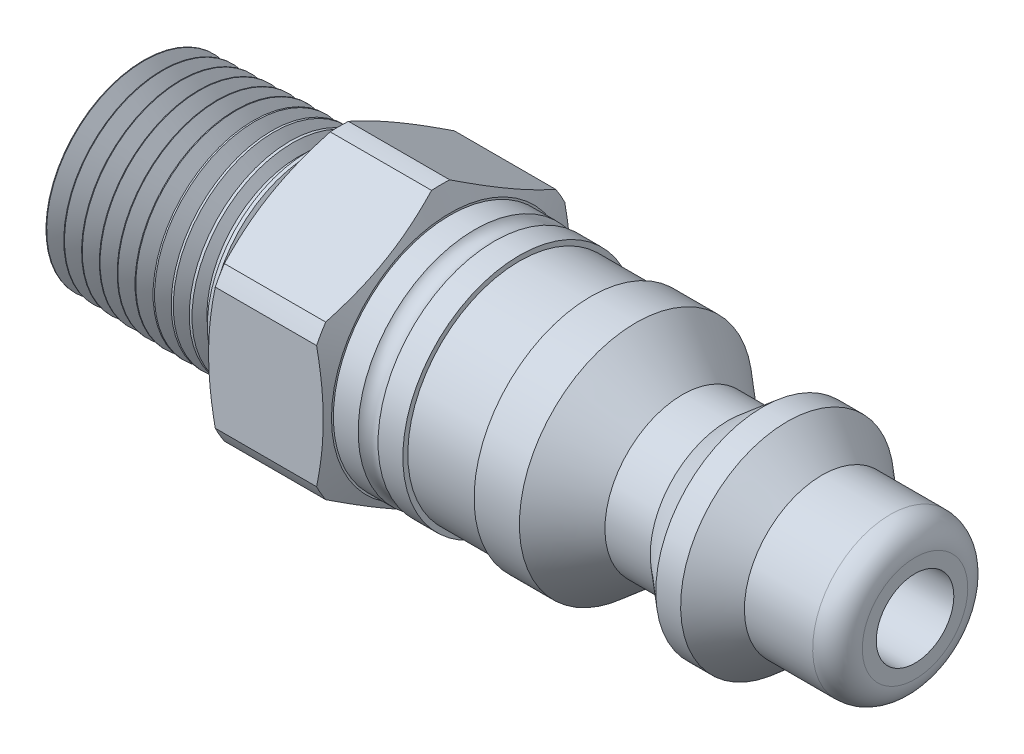
SolidWorks part; units mm, degrees
ref_plane "Front" through (0, 0, 0) normal (0, 0, 1) x (1, 0, 0)
ref_plane "Top" through (0, 0, 0) normal (0, 1, 0) x (1, 0, 0)
ref_plane "Right" through (0, 0, 0) normal (1, 0, 0) x (0, 0, -1)
sketch "Sketch1" plane through (0, 0, 0) normal (0, 0, 1) x (1, 0, 0)
  line L0 (0, 0) -> (0, 4.2025)
  line L1 (0, 4.2025) -> (0.4447, 5.0315) construction
  line L2 (0.4447, 5.0315) -> (0.9403, 4.2319) construction
  line L3 (0.9403, 4.2319) -> (1.385, 5.0609) construction
  line L4 (1.385, 5.0609) -> (1.8806, 4.2613) construction
  line L5 (0.9572, 4.2635) -> (1.368, 5.0293)
  line L6 (1.368, 5.0293) -> (1.4039, 5.0304)
  line L7 (1.4039, 5.0304) -> (1.8617, 4.2918)
  line L8 (1.8617, 4.2918) -> (1.8975, 4.2929)
  line L9 (0, 4.2025) -> (1.8806, 4.2613) construction
  line L10 (0.4447, 5.0315) -> (1.385, 5.0609) construction
  line L11 (0.2223, 4.617) -> (1.6328, 4.6611) construction
  line L12 (0, 0) -> (-4.2025, 0) construction
  line L13 (1.8975, 4.2929) -> (2.3083, 5.0587)
  line L14 (0.017, 4.2342) -> (0.4277, 4.9999)
  line L15 (0.4277, 4.9999) -> (0.4636, 5.0011)
  line L16 (0.4636, 5.0011) -> (0.9214, 4.2624)
  line L17 (0.9214, 4.2624) -> (0.9572, 4.2635)
  line L18 (0.2223, 4.617) -> (0, 4.6101) construction
  line L19 (0, 4.6101) -> (0, 4.2025) construction
  line L20 (0.2223, -4.617) -> (0, -4.6101) construction
  line L21 (0.017, 4.2342) -> (0, 4.2025)
  line L22 (2.3083, 5.0587) -> (2.3441, 5.0598)
  line L23 (2.3441, 5.0598) -> (2.802, 4.3212)
  line L24 (2.802, 4.3212) -> (2.8378, 4.3223)
  line L25 (2.8378, 4.3223) -> (3.2486, 5.0881)
  line L26 (3.2486, 5.0881) -> (3.2844, 5.0892)
  line L27 (3.2844, 5.0892) -> (3.7422, 4.3506)
  line L28 (3.7422, 4.3506) -> (3.7781, 4.3517)
  line L29 (3.7781, 4.3517) -> (4.1889, 5.1175)
  line L30 (4.1889, 5.1175) -> (4.2247, 5.1186)
  line L31 (4.2247, 5.1186) -> (4.6825, 4.38)
  line L32 (4.6825, 4.38) -> (4.7184, 4.3811)
  line L33 (4.7184, 4.3811) -> (5.1291, 5.1469)
  line L34 (5.1291, 5.1469) -> (5.165, 5.148)
  line L35 (5.165, 5.148) -> (5.6228, 4.4093)
  line L36 (5.6228, 4.4093) -> (5.6586, 4.4105)
  line L37 (5.6586, 4.4105) -> (6.0694, 5.1763)
  line L38 (6.0694, 5.1763) -> (6.1053, 5.1774)
  line L39 (6.1053, 5.1774) -> (6.5631, 4.4387)
  line L40 (6.5631, 4.4387) -> (6.5989, 4.4398)
  line L41 (6.5989, 4.4398) -> (7.0097, 5.2056)
  line L42 (7.0097, 5.2056) -> (7.0456, 5.2068)
  line L43 (7.0456, 5.2068) -> (7.5034, 4.4681)
  line L44 (7.5034, 4.4681) -> (7.5392, 4.4692)
  line L45 (7.5392, 4.4692) -> (7.95, 5.235)
  line L46 (7.95, 5.235) -> (7.9858, 5.2361)
  line L47 (7.9858, 5.2361) -> (8.4436, 4.4975)
  line L48 (8.4436, 4.4975) -> (8.4795, 4.4986)
  line L49 (8.4795, 4.4986) -> (8.8903, 5.2644)
  line L50 (8.8903, 5.2644) -> (8.9261, 5.2655)
  line L51 (8.9261, 5.2655) -> (9.3839, 4.5269)
  line L52 (9.3839, 4.5269) -> (9.4198, 4.528)
  line L53 (9.4198, 4.528) -> (9.8306, 5.2938)
  line L54 (9.8306, 5.2938) -> (9.8664, 5.2949)
  line L55 (9.8664, 5.2949) -> (10.3242, 4.5563)
  line L56 (10.3242, 4.5563) -> (10.3601, 4.5574)
  line L57 (10.3601, 4.5574) -> (10.7708, 5.3232)
  line L58 (10.7708, 5.3232) -> (10.8067, 5.3243)
  line L59 (10.8067, 5.3243) -> (11.2645, 4.5857)
  line L60 (11.2645, 4.5857) -> (11.3003, 4.5868)
  line L61 (0, 0) -> (39.9, 0) construction
  line L62 (0, 3.4163) -> (0, -3.4163) construction
  line L73 (0, 0) -> (11.3003, 0)
  line L74 (11.3003, 0) -> (11.3003, 4.5868)
  line L75 (0.4457, 5.0005) -> (0.4447, 5.0315) construction
  line L76 (1.6328, 4.6611) -> (6.7056, 4.8197) construction
  line L77 (6.7056, 4.8197) -> (6.7056, 0) construction
  line L78 (6.7056, 4.8197) -> (9.967, 4.9216) construction
  line L79 (9.967, 4.9216) -> (9.967, 0) construction
  line L80 (9.967, 4.9216) -> (9.967, 5.1435) construction
  line L81 (9.967, 5.1435) -> (11.3003, 5.1435) construction
  line L82 (11.3003, 5.1435) -> (11.3003, 4.5868) construction
  line L84 (6.7056, 4.4432) -> (9.967, 4.5451) construction
  line L87 (9.967, 4.2025) -> (0, 4.2025) construction
  point P75 (16.1002, 0)
  dimension "D1" = 60
  dimension "D2" = 0.031
  dimension "E0" = 9.2202
  dimension "D3" = 0.0359
  dimension "Thread Pitch" = 0.9407
  dimension "D4" = 3.58
  dimension "L2 Thread Engagement" = 6.7056
  dimension "L4 Thread Length" = 9.967
  dimension "ID" = 6.8326
  dimension "Pipe OD" = 10.287
  dimension "Length" = 39.9
  dimension "Plug End" = 23.7998
revolve "Revolve1" add sketch "Sketch1" angle 360 about L12
sketch "Sketch5" plane through (0, 0, 0) normal (0, 0, 1) x (1, 0, 0)
  line L0 (9.967, 0) -> (9.967, 5.2981)
  line L1 (9.967, 5.2981) -> (11.3003, 5.3397)
  line L2 (11.3003, 5.3397) -> (11.3003, 0)
  line L3 (11.3003, 0) -> (9.967, 0)
  line L4 (0, 0) -> (-4.2025, 0) construction
  line L5 (0, 0) -> (-4.2025, 0) construction
  line L6 (9.967, 4.9216) -> (9.967, 0) construction
  line L8 (10.7708, 5.3232) -> (10.8067, 5.3243) construction
  line L9 (11.3003, 5.1435) -> (11.3003, 4.5868) construction
  line L16 (0, 0) -> (39.9, 0) construction
revolve "Cut-Revolve2" cut sketch "Sketch5" angle 360 about L5
sketch "Sketch6" plane through (0, 0, 0) normal (0, 0, 1) x (1, 0, 0)
  line L0 (0, 0) -> (0, 4.2025) construction
  line L1 (11.3003, 5.1435) -> (0, 5.1435)
  line L2 (11.3003, 5.1435) -> (11.3003, 20.6399)
  line L3 (11.3003, 20.6399) -> (0, 20.6399)
  line L4 (0, 5.1435) -> (0, 20.6399)
revolve "Cut-Revolve3" cut sketch "Sketch6" angle 360 about L61
sketch "Sketch7" plane through (0, 0, 0) normal (0, 0, 1) x (1, 0, 0)
  line L0 (6.7056, 4.2025) -> (9.967, 5.1435)
  line L1 (6.7056, 4.8197) -> (6.7056, 0) construction
  line L2 (9.967, 4.2025) -> (0, 4.2025) construction
  line L3 (9.967, 5.1435) -> (9.967, 4.2025)
  line L4 (9.967, 4.2025) -> (6.7056, 4.2025)
revolve "Revolve2" add sketch "Sketch7" angle 360 about L61
sketch "Sketch8" plane through (9.967, 0, 0) normal (1, 0, 0) x (0, 0, -1)
  line L1 (0, 7.3323) -> (-6.35, 3.6662)
  line L2 (-6.35, 3.6662) -> (-6.35, -3.6662)
  line L3 (-6.35, -3.6662) -> (0, -7.3323)
  line L4 (0, -7.3323) -> (6.35, -3.6662)
  line L5 (6.35, -3.6662) -> (6.35, 3.6662)
  line L6 (6.35, 3.6662) -> (0, 7.3323)
  circle A0 centre (0, 0) radius 6.35 construction
  dimension "Hex" = 12.7
extrude "Extrude1" add sketch "Sketch8" along normal up to vertex (6.1332 mm away) up to point (16.1002, 0, 0)
sketch "Sketch9" plane through (0, 0, 0) normal (0, 0, 1) x (1, 0, 0)
  line L0 (16.1002, 6.0623) -> (15.6264, 7.0783)
  line L1 (16.1002, 3.6662) -> (16.1002, 7.3323) construction
  line L2 (15.6264, 7.0783) -> (10.4407, 7.0783)
  line L3 (10.4407, 7.0783) -> (9.967, 6.0623)
  line L4 (9.967, 3.6662) -> (9.967, 7.3323) construction
  line L5 (9.967, 6.0623) -> (9.967, 7.3323)
  line L6 (9.967, 7.3323) -> (16.1002, 7.3323)
  line L7 (16.1002, 7.3323) -> (16.1002, 6.0623)
  dimension "D1" = 25
  dimension "D2" = 0.254
  dimension "D3" = 1.27
revolve "Cut-Revolve4" cut sketch "Sketch9" angle 360 about L61
sketch "Sketch10" plane through (0, 0, 0) normal (0, 0, 1) x (1, 0, 0)
  line L0 (16.1002, 0) -> (39.9, 0)
  line L1 (39.9, 0) -> (39.9, 3.9688)
  line L2 (39.9, 3.9688) -> (35.1375, 3.9688)
  line L3 (35.1375, 3.9688) -> (33.3624, 5.4582)
  line L4 (33.3624, 5.4582) -> (32.0924, 5.4582)
  line L5 (32.0924, 5.4582) -> (30.3173, 3.9688)
  line L6 (30.3173, 3.9688) -> (28.0001, 3.9688)
  line L7 (28.0001, 3.9688) -> (25.6196, 5.9662)
  line L8 (25.6196, 5.9662) -> (23.3024, 5.9662)
  line L9 (16.1002, -6.0623) -> (16.1002, 6.0623) construction
  line L10 (16.1002, 5.9662) -> (16.1002, 0)
  line L11 (39.9, 3.9688) -> (39.9, -3.9688) construction
  line L12 (23.3024, 5.9662) -> (23.3024, 5.7122)
  line L13 (23.3024, 5.7122) -> (19.6562, 5.7122)
  line L14 (19.6562, 5.7122) -> (19.6562, 5.9662)
  line L15 (19.6562, 5.9662) -> (18.3862, 5.9662)
  line L16 (17.3702, 5.9662) -> (16.1002, 5.9662)
  line L17 (19.6562, 5.7122) -> (17.8782, 5.7122) construction
  line L18 (25.6196, 5.9662) -> (32.7274, 5.9662) construction
  line L19 (32.7274, 5.9662) -> (32.7274, 5.4582) construction
  line L20 (28.0001, 3.9688) -> (28.0001, 0) construction
  arc A0 (18.3862, 5.9662) -> (17.3702, 5.9662) centre (17.8782, 6.3472) cw
  point P25 (32.7274, 5.7122)
  dimension "D3" = 100
  dimension "D4" = 0.635
  dimension "D1" = 0.254
  dimension "A" = 7.9375
  dimension "B" = 4.7625
  dimension "D2" = 1.27
revolve "Revolve3" add sketch "Sketch10" angle 360 about L12
fillet "Fillet1" radius 1.27 1 edges at (39.9, 3.9688, 0)
sketch "Sketch11" plane through (0, 0, 0) normal (0, 0, 1) x (1, 0, 0)
  line L0 (9.967, 3.4163) -> (16.1002, 1.9844)
  line L1 (0, 3.4163) -> (9.967, 3.4163)
  line L2 (0, 3.4163) -> (0, 0)
  line L3 (0, 0) -> (6.7056, 0)
  line L4 (16.1002, 1.9844) -> (39.9, 1.9844)
  line L5 (9.967, 4.9216) -> (9.967, 0) construction
  line L6 (39.9, 0) -> (39.9, 3.9688) construction
  line L8 (39.9, 1.9844) -> (39.9, 0)
  line L9 (39.9, 0) -> (6.7056, 0)
  line L12 (16.1002, 5.9662) -> (16.1002, 0) construction
  point P6 (0, 1.7082)
revolve "Cut-Revolve5" cut sketch "Sketch11" angle 360 about L12
equation "\"D2@Sketch1\"=\"Thread Pitch@Sketch1\"*.033"
